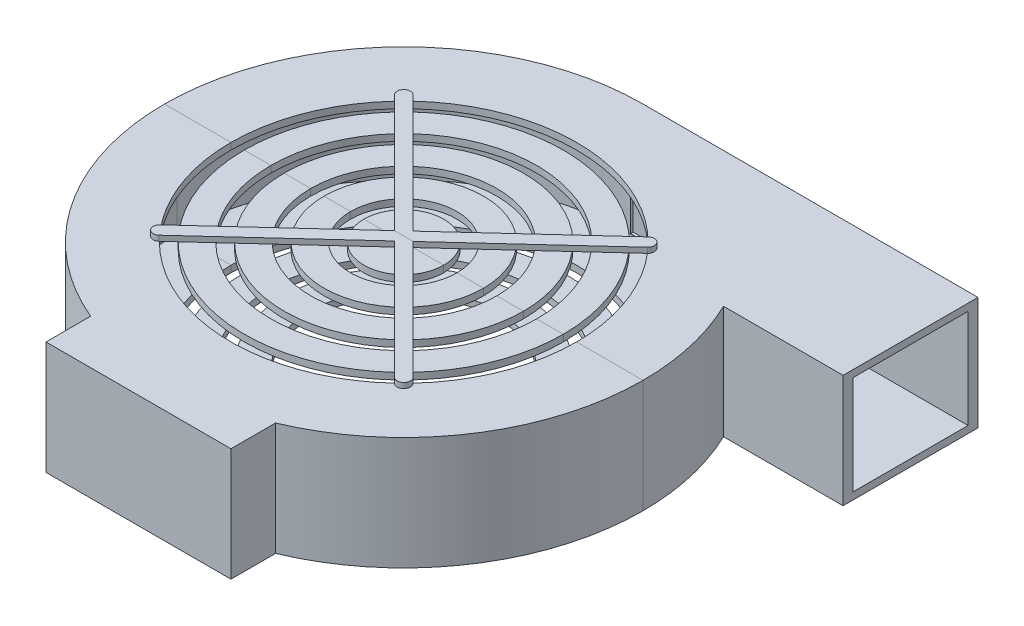
SolidWorks part; units mm, degrees
ref_plane "Płaszczyzna przednia" through (0, 0, 0) normal (0, 0, 1) x (1, 0, 0)
ref_plane "Płaszczyzna górna" through (0, 0, 0) normal (0, 1, 0) x (1, 0, 0)
ref_plane "Płaszczyzna prawa" through (0, 0, 0) normal (1, 0, 0) x (0, 0, -1)
sketch "Szkic1" plane through (0, 0, 0) normal (0, 1, 0) x (1, 0, 0)
  line L0 (0, 0) -> (-40.9091, 0) construction
  line L1 (-20.4545, 0) -> (-20.4545, 28.9703) construction
  line L2 (49.1068, 0) -> (-90.0159, 0)
  line L3 (-90.0159, 0) -> (-90.0159, 33.5709)
  line L5 (49.1068, 45) -> (49.1068, 43.7947)
  line L6 (-20.4545, 28.9703) -> (-20.4545, 199.5866) construction
  line L7 (49.1068, 33.5709) -> (49.1068, 0)
  line L8 (-90.0159, 43.7947) -> (-90.0159, 45)
  line L9 (141.5203, 278.0987) -> (231.5203, 278.0987)
  line L10 (-20.4545, 379.5866) -> (231.5203, 379.5866)
  line L11 (231.5203, 379.5866) -> (231.5203, 278.0987)
  circle A0 centre (-20.4545, 199.5866) radius 170.6163
  circle A1 centre (-20.4545, 199.5866) radius 180
  circle A2 centre (-20.4545, 199.5866) radius 120
  circle A3 centre (-20.4545, 199.5866) radius 110
  circle A4 centre (-20.4545, 199.5866) radius 90
  circle A5 centre (-20.4545, 199.5866) radius 80
  circle A6 centre (-20.4545, 199.5866) radius 60
  circle A7 centre (-20.4545, 199.5866) radius 50
  circle A8 centre (-20.4545, 199.5866) radius 30
  circle A9 centre (-20.4545, 199.5866) radius 20
  point P8 (-20.4545, 0)
  dimension "D2" = 90
  dimension "D1" = 45
extrude "Dodanie-wyciągnięcie2" add sketch "Szkic1" along normal blind 85 contours A1 A0 | A1 L9 L11 L10 | A1 L3 L2 L7
sketch "Szkic2" plane through (0, 0, 0) normal (0, 1, 0) x (1, 0, 0)
  circle A0 centre (-20.4545, 199.5866) radius 130
  circle A2 centre (-20.4545, 199.5866) radius 170.6163
extrude "Dodanie-wyciągnięcie3" add sketch "Szkic2" along normal blind 5
ref_plane "Płaszczyzna1" through (0, 85, 0) normal (0, -1, 0) x (-1, 0, 0)
sketch "Szkic3" plane through (0, 85, 0) normal (0, -1, 0) x (-1, 0, 0)
  circle A0 centre (20.4545, 199.5866) radius 170.6163
  circle A1 centre (20.4545, 199.5866) radius 130
extrude "Dodanie-wyciągnięcie6" add sketch "Szkic3" along normal blind 5
sketch "Szkic4" plane through (0, 85, 0) normal (0, -1, 0) x (-1, 0, 0)
  circle A0 centre (20.4545, 199.5866) radius 120
  circle A1 centre (20.4545, 199.5866) radius 100
  circle A2 centre (20.4545, 199.5866) radius 90
  circle A3 centre (20.4545, 199.5866) radius 70
  circle A4 centre (20.4545, 199.5866) radius 60
  circle A5 centre (20.4545, 199.5866) radius 40
  circle A6 centre (20.4545, 199.5866) radius 30
extrude "Dodanie-wyciągnięcie7" add sketch "Szkic4" along normal blind 5 separate body contours A0 A1 | A2 A3 | A4 A5 | A6
sketch "Szkic5" plane through (0, 0, 0) normal (0, 1, 0) x (1, 0, 0)
  circle A0 centre (-20.4545, 199.5866) radius 120
  circle A1 centre (-20.4545, 199.5866) radius 100
  circle A2 centre (-20.4545, 199.5866) radius 90
  circle A3 centre (-20.4545, 199.5866) radius 70
  circle A4 centre (-20.4545, 199.5866) radius 60
  circle A5 centre (-20.4545, 199.5866) radius 40
  circle A6 centre (-20.4545, 199.5866) radius 30
extrude "Dodanie-wyciągnięcie8" add sketch "Szkic5" along normal blind 5 separate body contours A0 A1 | A2 A3 | A4 A5 | A6
ref_plane "Płaszczyzna2" through (231.5203, 0, 0) normal (1, 0, 0) x (0, 0, -1)
sketch "Szkic6" plane through (231.5203, 0, 0) normal (1, 0, 0) x (0, 0, -1)
  line L0 (285.6552, 79.7019) -> (285.6552, 5.2981)
  line L1 (285.6552, 5.2981) -> (372.1395, 5.2981)
  line L2 (372.1395, 5.2981) -> (372.1395, 79.7019)
  line L3 (372.1395, 79.7019) -> (285.6552, 79.7019)
  point P3 (285.6552, 42.5)
extrude "Wytnij-wyciągnięcie2" cut sketch "Szkic6" against normal blind 252
sketch "Szkic8" plane through (0, 85, 0) normal (0, -1, 0) x (-1, 0, 0)
  line L0 (13.828, 205.6695) -> (116.2239, 111.6762) construction
  line L1 (-72.0895, 291.0107) -> (20.1828, 206.3103)
  line L2 (-78.54, 283.9835) -> (13.4316, 199.5591)
  line L3 (112.3784, 291.5105) -> (-71.4693, 107.6628) construction
  line L4 (115.8761, 288.0128) -> (27.4775, 199.6142)
  line L5 (108.8807, 295.0082) -> (20.1828, 206.3103)
  line L6 (20.7263, 192.863) -> (112.9986, 108.1626)
  line L7 (27.4775, 199.6142) -> (119.4491, 115.1898)
  line L8 (13.4316, 199.5591) -> (-74.967, 111.1605)
  line L9 (20.7263, 192.863) -> (-67.9716, 104.1651)
  circle A0 centre (20.4545, 199.5866) radius 130 construction
  arc A1 (-72.0895, 291.0107) -> (-78.54, 283.9835) centre (-75.3148, 287.4971) ccw
  arc A2 (112.9986, 108.1626) -> (119.4491, 115.1898) centre (116.2239, 111.6762) ccw
  arc A3 (115.8761, 288.0128) -> (108.8807, 295.0082) centre (112.3784, 291.5105) ccw
  arc A4 (-74.967, 111.1605) -> (-67.9716, 104.1651) centre (-71.4693, 107.6628) ccw
  point P5 (20.4545, 199.5866)
  point P11 (20.4545, 199.5866)
extrude "Dodanie-wyciągnięcie9" add sketch "Szkic8" against normal blind 4
ref_plane "Płaszczyzna3" through (0, -10, 0) normal (0, -1, 0) x (-1, 0, 0)
sketch "Szkic9" plane through (0, -10, 0) normal (0, -1, 0) x (-1, 0, 0)
  circle A0 centre (20.4545, 199.5866) radius 70.3321
extrude "Wytnij-wyciągnięcie4" cut sketch "Szkic9" against normal blind 20
sketch "Szkic11" plane through (0, -10, 0) normal (0, -1, 0) x (-1, 0, 0)
  line L0 (20.4545, 199.5866) -> (218.0934, 199.5866)
  line L1 (218.0934, 199.5866) -> (-250.4192, 199.5866)
ref_plane "Płaszczyzna5" through (0, 0, -199.5866) normal (0, 0, 1) x (1, 0, 0)
split "Podziel2" trim tools "Płaszczyzna5" bodies to split 121 resulting bodies 129 130
